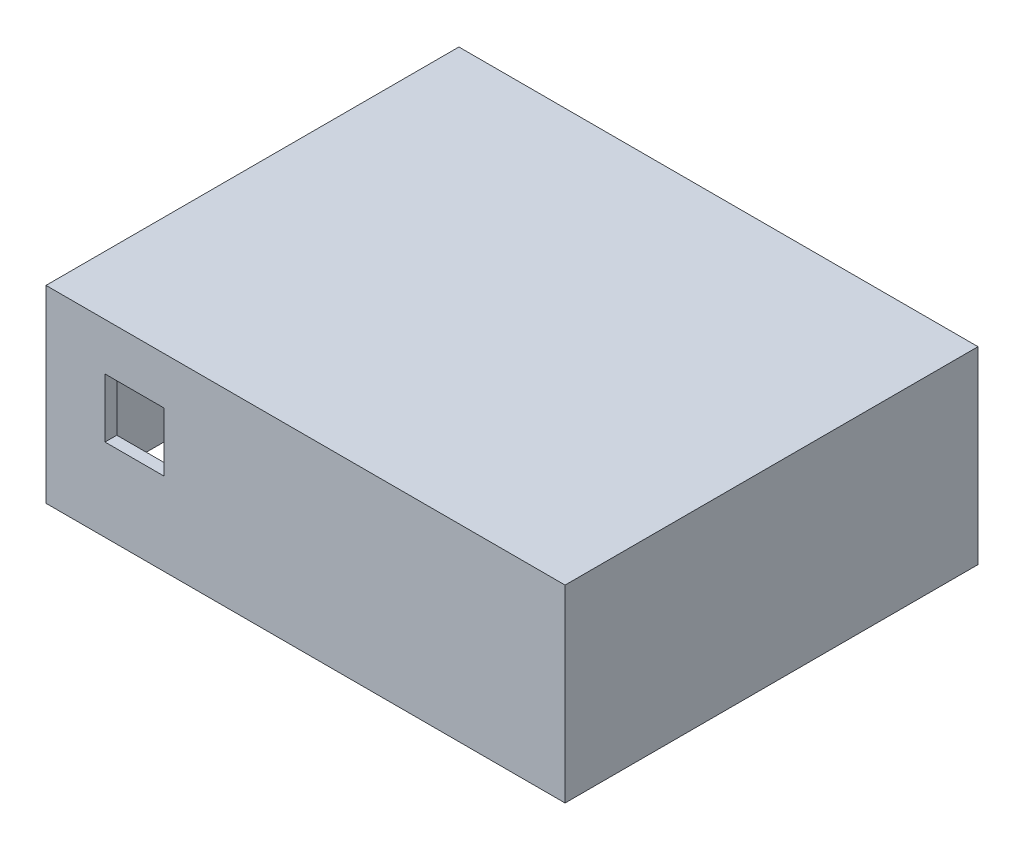
SolidWorks part; units mm, degrees
ref_plane "Front Plane" through (0, 0, 0) normal (0, 0, 1) x (1, 0, 0)
ref_plane "Top Plane" through (0, 0, 0) normal (0, 1, 0) x (1, 0, 0)
ref_plane "Right Plane" through (0, 0, 0) normal (1, 0, 0) x (0, 0, -1)
sketch "Sketch1" plane through (0, 0, 0) normal (0, 1, 0) x (1, 0, 0)
  line L1 (44, -35) -> (-44, -35)
  line L2 (44, -35) -> (44, 35)
  line L3 (44, 35) -> (-44, 35)
  line L4 (-44, -35) -> (-44, 35)
  line L5 (44, -35) -> (-44, 35) construction
  line L6 (44, 35) -> (-44, -35) construction
  point P0 (0, 0)
  dimension "D1" = 70
  dimension "D2" = 88
extrude "Boss-Extrude1" add sketch "Sketch1" along normal blind 32
sketch "Sketch2" plane through (0, 0, 0) normal (0, 1, 0) x (1, 0, 0)
  line L1 (-42, -33) -> (42, -33)
  line L2 (-42, -33) -> (-42, 33)
  line L3 (-42, 33) -> (42, 33)
  line L4 (42, -33) -> (42, 33)
  line L5 (-42, -33) -> (42, 33) construction
  line L6 (-42, 33) -> (42, -33) construction
  point P0 (0, 0)
  dimension "D1" = 66
  dimension "D2" = 84
extrude "Cut-Extrude1" cut sketch "Sketch2" along normal blind 30
sketch "Sketch4" plane through (0, 0, -35) normal (0, 0, -1) x (-1, 0, 0)
  line L0 (-44, 32) -> (-44, 0) construction
  line L1 (-14, 22) -> (-39, 22)
  line L2 (-14, 22) -> (-14, 28.5)
  line L3 (-14, 28.5) -> (-39, 28.5)
  line L4 (-39, 22) -> (-39, 28.5)
  line L5 (37.9, 24.08) -> (37.9, 18.3)
  line L6 (40.46, 24.08) -> (40.46, 18.3)
  line L7 (-44, 32) -> (44, 32) construction
  line L8 (44, 32) -> (44, 0) construction
  line L9 (-10, 1.5) -> (-16, 1.5)
  line L10 (-10, 1.5) -> (-10, 7.5)
  line L11 (-10, 7.5) -> (-16, 7.5)
  line L12 (-16, 1.5) -> (-16, 7.5)
  line L13 (-10, 1.5) -> (-16, 7.5) construction
  line L14 (-10, 7.5) -> (-16, 1.5) construction
  line L15 (24, 9) -> (14, 9)
  line L16 (24, 9) -> (24, 25.5)
  line L17 (24, 25.5) -> (14, 25.5)
  line L18 (14, 9) -> (14, 25.5)
  line L19 (24, 9) -> (14, 25.5) construction
  line L20 (24, 25.5) -> (14, 9) construction
  arc A0 (37.9, 24.08) -> (40.46, 24.08) centre (39.18, 24.08) cw
  arc A1 (37.9, 18.3) -> (40.46, 18.3) centre (39.18, 18.3) ccw
  point P0 (-26.5, 25.25)
  point P9 (-13, 4.5)
  point P14 (-13, 7.5)
  point P15 (19, 17.25)
  point P28 (40.46, 21.19)
  point P29 (39.18, 25.36)
  dimension "D15" = 3.54
  dimension "D16" = 6.64
  dimension "D1" = 25
  dimension "D2" = 6.5
  dimension "D3" = 5
  dimension "D4" = 3.5
  dimension "D5" = 6
  dimension "D6" = 6
  dimension "D7" = 14.5
  dimension "D8" = 2
  dimension "D9" = 10
  dimension "D10" = 16.5
  dimension "D11" = 5.78
  dimension "D12" = 2.56
  dimension "D13" = 6.5
  dimension "D14" = 20
extrude "Cut-Extrude2" cut sketch "Sketch4" against normal blind 3
sketch "Sketch6" plane through (0, 0, 35) normal (0, 0, 1) x (1, 0, 0)
  line L0 (-44, 32) -> (-44, 0) construction
  line L1 (-24, 14) -> (-34, 14)
  line L2 (-24, 14) -> (-24, 24)
  line L3 (-24, 24) -> (-34, 24)
  line L4 (-34, 14) -> (-34, 24)
  line L5 (-24, 14) -> (-34, 24) construction
  line L6 (-24, 24) -> (-34, 14) construction
  line L7 (-44, 0) -> (44, 0) construction
  point P0 (-29, 19)
  dimension "D1" = 10
  dimension "D2" = 10
  dimension "D3" = 10
  dimension "D4" = 14
extrude "Cut-Extrude3" cut sketch "Sketch6" against normal blind 3
sketch "Sketch7" plane through (0, 0, 0) normal (0, -1, 0) x (1, 0, 0)
  line L1 (43, -34) -> (-43, -34)
  line L2 (43, -34) -> (43, 34)
  line L3 (43, 34) -> (-43, 34)
  line L4 (-43, -34) -> (-43, 34)
  line L5 (43, -34) -> (-43, 34) construction
  line L6 (43, 34) -> (-43, -34) construction
  point P0 (0, 0)
  dimension "D1" = 68
  dimension "D2" = 86
extrude "Cut-Extrude4" cut sketch "Sketch7" against normal blind 1
sketch "Sketch10" plane through (0, 0, -35) normal (0, 0, -1) x (-1, 0, 0)
  line L0 (-44, 32) -> (-44, 0) construction
  line L1 (-39, 28.5) -> (-14, 28.5)
  line L2 (-39, 28.5) -> (-39, 22)
  line L3 (-39, 22) -> (-14, 22)
  line L4 (-14, 28.5) -> (-14, 22)
  line L5 (-39, 28.5) -> (-14, 22) construction
  line L6 (-39, 22) -> (-14, 28.5) construction
  line L8 (-44, 32) -> (44, 32) construction
  line L10 (-16, 7.5) -> (-10, 7.5)
  line L11 (-16, 7.5) -> (-16, 1.5)
  line L12 (-16, 1.5) -> (-10, 1.5)
  line L13 (-10, 7.5) -> (-10, 1.5)
  line L14 (-16, 7.5) -> (-10, 1.5) construction
  line L15 (-16, 1.5) -> (-10, 7.5) construction
  point P0 (-26.5, 25.25)
  point P7 (-13, 4.5)
  dimension "D1" = 25
  dimension "D2" = 6.5
  dimension "D3" = 5
  dimension "D4" = 3.5
  dimension "D5" = 6
  dimension "D6" = 6
  dimension "D7" = 14.5
  dimension "D8" = 2
extrude "Cut-Extrude5" cut sketch "Sketch10" against normal blind 3
sketch "Sketch11" plane through (0, 30, 0) normal (0, -1, 0) x (1, 0, 0)
  line L0 (-42, 33) -> (-42, -33) construction
  line L1 (42, 33) -> (-42, 33) construction
  line L2 (-42, 33) -> (42, 33) construction
  line L3 (42, -33) -> (42, 33) construction
  line L4 (38, 33) -> (42, 33)
  line L5 (42, 33) -> (42, 29)
  line L6 (-42, 33) -> (-42, -33)
  line L7 (42, 33) -> (-42, 33)
  line L8 (42, -33) -> (42, 33)
  line L9 (-42, -33) -> (42, -33)
  line L10 (-42, 33) -> (-42, 29)
  line L11 (-38, 33) -> (-42, 33)
  line L14 (42, 33) -> (42, -33) construction
  line L15 (-42, -33) -> (42, -33) construction
  line L16 (42, -29.5) -> (42, -33)
  line L17 (42, -33) -> (38.5, -33)
  line L18 (-35.5, -33) -> (-27.5, -33)
  arc A0 (-42, 29) -> (-38, 33) centre (-42, 33) ccw
  arc A1 (38, 33) -> (42, 29) centre (42, 33) ccw
  arc A2 (42, -29.5) -> (38.5, -33) centre (42, -33) ccw
  arc A3 (-35.5, -33) -> (-27.5, -33) centre (-31.5, -33) cw
  dimension "D1" = 4
  dimension "D4" = 4
  dimension "D5" = 3.5
  dimension "D6" = 4
  dimension "D2" = 0
  dimension "D7" = 6.5
  dimension "D3" = 0
extrude "Boss-Extrude2" add sketch "Sketch11" along normal blind 30
sketch "Sketch16" plane through (0, 0, 0) normal (0, -1, 0) x (-1, 0, 0)
  line L3 (-42, -33) -> (-38, -33) construction
  line L4 (38, -33) -> (42, -33) construction
  line L6 (-42, 33) -> (-38.5, 33) construction
  line L7 (-42, 33) -> (-42, 29.5) construction
  line L8 (35.5, 33) -> (27.5, 33) construction
  line L9 (42, 33) -> (42, -29) construction
  circle A0 centre (-41, 31) radius 0.6
  circle A1 centre (-40, -32) radius 0.6
  circle A2 centre (40.2679, -32) radius 0.6
  circle A3 centre (31.5, 31) radius 0.6
  dimension "D1" = 1.2
  dimension "D3" = 1
  dimension "D4" = 1.2
  dimension "D6" = 1
  dimension "D7" = 1.2
  dimension "D9" = 2
  dimension "D10" = 1
  dimension "D11" = 1.2
  dimension "D12" = 2
  dimension "D13" = 10.5
  dimension "D2" = 2
  dimension "D5" = 2
  dimension "D8" = 2
hole_wizard "Ø2.0mm Dowel Hole1" positions "Sketch17" profile "Sketch18" hole size "Ø1.5" standard "DIN"
sketch "Sketch17" plane through (0, 0, 0) normal (0, -1, 0) x (-1, 0, 0)
  point P0 (-41, 31)
  point P3 (31.5, 31)
  point P6 (40.2679, -32)
  point P9 (-40, -32)
sketch "Sketch18" plane through (41, 0, -31) normal (1, 0, 0) x (0, 0, -1)
  line L0 (0, 0) -> (0, 3.2)
  line L1 (0, 3.2) -> (0.75, 2.7494)
  line L2 (0.75, 2.7494) -> (0.75, 0)
  line L5 (0.75, 0) -> (0, 0)
  line L10 (0, 3.2) -> (-0.75, 2.7494) construction
  line L11 (0, -6.35) -> (0, 107.95) construction
  dimension "Hole Dia." = 1.5
  dimension "Hole Depth" = 3.2
  dimension "Drill Angle" = 118
sketch "Sketch21" plane through (0, 0, -35) normal (0, 0, -1) x (-1, 0, 0)
sketch "Sketch22" plane through (0, 0, -35) normal (0, 0, -1) x (-1, 0, 0)
  line L0 (37.9, 24.08) -> (37.9, 18.3)
  line L1 (40.46, 24.08) -> (40.46, 18.3)
  line L2 (-44, 32) -> (44, 32) construction
  line L3 (44, 32) -> (44, 0) construction
  arc A0 (37.9, 24.08) -> (40.46, 24.08) centre (39.18, 24.08) cw
  arc A1 (37.9, 18.3) -> (40.46, 18.3) centre (39.18, 18.3) ccw
  point P8 (39.18, 25.36)
  dimension "D1" = 5.78
  dimension "D2" = 2.56
  dimension "D3" = 6.64
  dimension "D4" = 3.54
extrude "Cut-Extrude6" cut sketch "Sketch22" against normal blind 3
